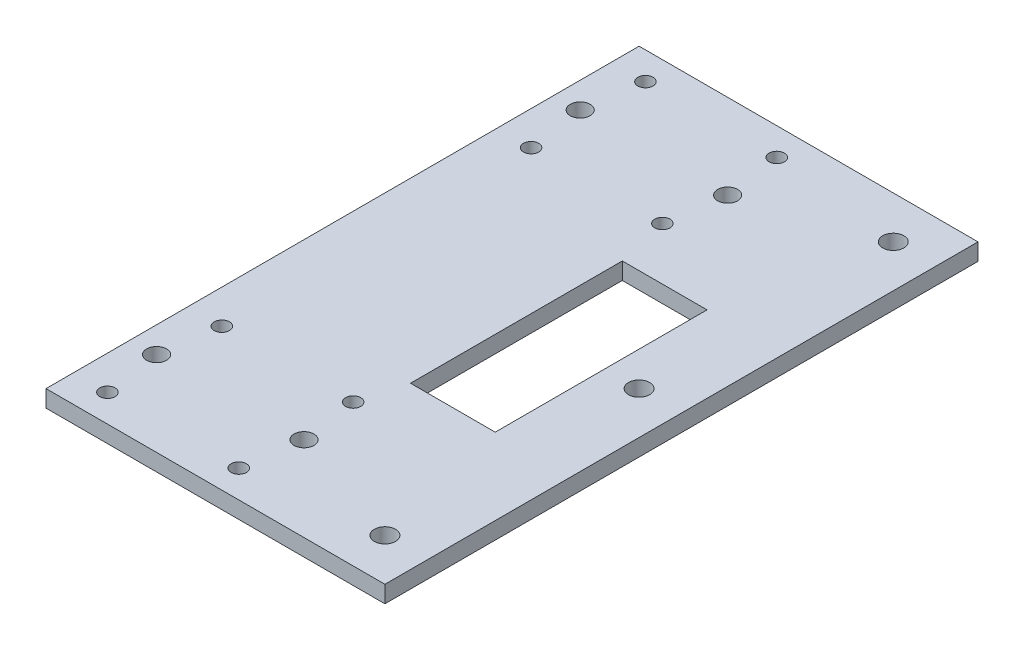
SolidWorks part; units mm, degrees
ref_plane "前视基准面" through (0, 0, 0) normal (0, 0, 1) x (1, 0, 0)
ref_plane "上视基准面" through (0, 0, 0) normal (0, 1, 0) x (1, 0, 0)
ref_plane "右视基准面" through (0, 0, 0) normal (1, 0, 0) x (0, 0, -1)
other "Configuration Table"
sketch "草图2" plane through (0, 0, 0) normal (0, 1, 0) x (1, 0, 0)
  line L0 (0, 70) -> (0, -70)
  line L1 (-80, -70) -> (80, -70)
  line L2 (-80, -70) -> (-80, 70)
  line L3 (-80, 70) -> (80, 70)
  line L4 (80, -70) -> (80, 70)
  line L5 (-80, -70) -> (80, 70) construction
  line L6 (-80, 70) -> (80, -70) construction
  point P0 (0, 0)
  dimension "D1" = 140
  dimension "D2" = 160
extrude "凸台-拉伸1" add sketch "草图2" along normal blind 4 contours L3 L2 L1 L0
ref_plane "基准面1" through (0, 4, 0) normal (0, 1, 0) x (1, 0, 0)
sketch "草图3" plane through (0, 4, 0) normal (0, 1, 0) x (1, 0, 0)
  line L0 (-1080, 50) -> (48920, 50) construction
  line L1 (-80, 70) -> (-33, 70)
  line L2 (-80, 70) -> (-80, 30)
  line L3 (-80, 30) -> (-33, 30)
  line L4 (-33, 70) -> (-33, 30)
  line L5 (-80, -70) -> (-33, -70)
  line L6 (-80, -70) -> (-80, -30)
  line L7 (-80, -30) -> (-33, -30)
  line L8 (-33, -70) -> (-33, -30)
  line L9 (-56.5, 110.6134) -> (-56.5, 29.3866) construction
  line L10 (-80, 0) -> (49920, 0) construction
  line L11 (-80, -70) -> (-80, 70) construction
  line L12 (0, 70) -> (0, -70) construction
  line L13 (-80, 70) -> (0, 70) construction
  line L14 (0, 70) -> (-10, 70)
  line L15 (0, 70) -> (0, 60)
  line L16 (0, 60) -> (-10, 60)
  line L17 (-10, 70) -> (-10, 60)
  circle A0 centre (-72, 63.5) radius 1.8
  circle A1 centre (-41, 63.5) radius 1.8
  circle A2 centre (-41, 36.5) radius 1.8
  circle A3 centre (-72, 36.5) radius 1.8
  circle A4 centre (-41, -63.5) radius 1.8
  circle A5 centre (-41, -36.5) radius 1.8
  circle A6 centre (-72, -36.5) radius 1.8
  circle A7 centre (-72, -63.5) radius 1.8
  circle A8 centre (-73.9, 50) radius 2.35
  circle A9 centre (-73.9, -50) radius 2.35
  circle A10 centre (-39.1, -50) radius 2.35
  circle A11 centre (-39.1, 50) radius 2.35
  circle A12 centre (-10, 60) radius 2.5
  circle A13 centre (-10, 0) radius 2.5
  circle A14 centre (-10, -60) radius 2.5
  point P13 (-80, 50)
  point P18 (-56.5, 70)
  point P28 (-80, 0)
  point P31 (0, 0)
  point P55 (0, 0)
  dimension "D5" = 3.6
  dimension "D8" = 4.7
  dimension "D10" = 10
  dimension "D12" = 5
  dimension "D1" = 40
  dimension "D2" = 40
  dimension "D3" = 47
  dimension "D4" = 47
  dimension "D6" = 8
  dimension "D7" = 6.5
  dimension "D9" = 6.1
  dimension "D11" = 10
  dimension "D13" = 3
extrude "切除-拉伸3" cut sketch "草图3" against normal blind 4 contours A0 | A8 | A3 | A2 | A11 | A1 | L16 A12 L17 | L17 A12 L16 | A9 | A6 | A7 | A4 | A10 | A5 | A14 | A13
sketch "草图4" plane through (0, 0, 0) normal (0, -1, 0) x (1, 0, 0)
  line L1 (-38.0746, -24.1155) -> (-18.0746, -24.1155)
  line L2 (-38.0746, -24.1155) -> (-38.0746, 25.8845)
  line L3 (-38.0746, 25.8845) -> (-18.0746, 25.8845)
  line L4 (-18.0746, -24.1155) -> (-18.0746, 25.8845)
  line L5 (-38.0746, -24.1155) -> (-18.0746, 25.8845) construction
  line L6 (-38.0746, 25.8845) -> (-18.0746, -24.1155) construction
  point P0 (-28.0746, 0.8845)
  dimension "D1" = 20
  dimension "D2" = 50
extrude "切除-拉伸4" cut sketch "草图4" against normal up to next
